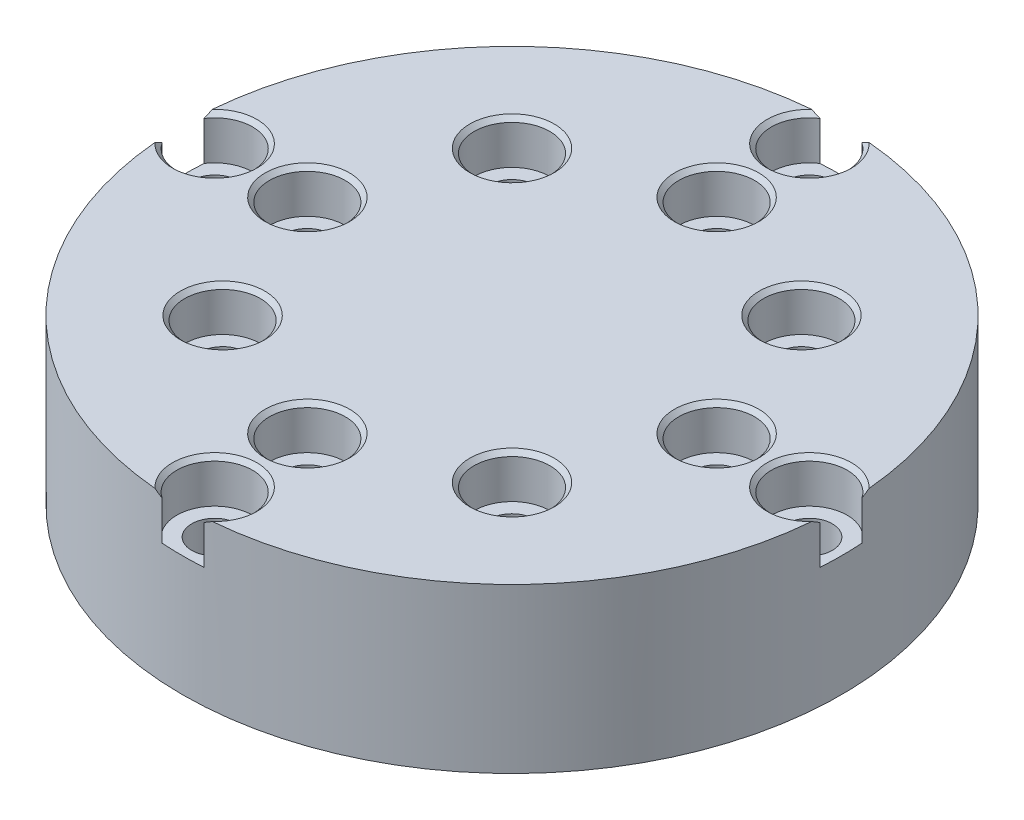
SolidWorks part; units mm, degrees
ref_plane "Front Plane" through (0, 0, 0) normal (0, 0, 1) x (1, 0, 0)
ref_plane "Top Plane" through (0, 0, 0) normal (0, 1, 0) x (1, 0, 0)
ref_plane "Right Plane" through (0, 0, 0) normal (1, 0, 0) x (0, 0, -1)
sketch "Sketch1" plane through (0, 0, 0) normal (0, 1, 0) x (1, 0, 0)
  circle A0 centre (0, 0) radius 48.3128
extrude "Boss-Extrude1" add sketch "Sketch1" along normal blind 24
sketch "Sketch2" plane through (0, 24, 0) normal (0, 1, 0) x (1, 0, 0)
  line L1 (24.7068, -14.1367) -> (-24.7068, -14.1367)
  line L2 (24.7068, -14.1367) -> (24.7068, 14.1367)
  line L3 (24.7068, 14.1367) -> (-24.7068, 14.1367)
  line L4 (-24.7068, -14.1367) -> (-24.7068, 14.1367)
  line L5 (24.7068, -14.1367) -> (-24.7068, 14.1367) construction
  line L6 (24.7068, 14.1367) -> (-24.7068, -14.1367) construction
  point P0 (0, 0)
hole_wizard "CBORE for 1/4 Socket Head Cap Screw1" positions "3DSketch1" profile "Sketch3" counterbore size "1/4" standard "ANSI Inch"
sketch3d "3DSketch1"
  line L0 (0, 24, 10) -> (0, 24, -10) construction
  point P2 (0, 24, 10)
  point P4 (-24.7068, 24, 14.1367)
  point P6 (-24.7068, 24, -14.1367)
  point P8 (24.7068, 24, -14.1367)
  point P10 (0, 24, -10)
  point P12 (24.7068, 24, 14.1367)
  point P31 (-12, 24, -0.1211)
  dimension "D1" = 20
  dimension "D2" = 12
sketch "Sketch3" plane through (0, 24, 10) normal (1, 0, 0) x (0, 0, 1)
  line L0 (0, 0) -> (0, 24)
  line L1 (0, 24) -> (3.3782, 24)
  line L3 (3.3782, 24) -> (3.3782, 6.35)
  line L4 (5.5562, 6.35) -> (3.3782, 6.35)
  line L5 (5.5562, 6.35) -> (5.5562, 0.635)
  line L6 (5.5562, 0.635) -> (6.1913, 0)
  line L7 (6.1913, 0) -> (0, 0)
  line L8 (-5.5562, 0.635) -> (-6.1913, 0) construction
  line L11 (0, -6.35) -> (0, 107.95) construction
  dimension "Thru Hole Dia." = 6.7564
  dimension "Thru Hole Depth" = 24
  dimension "C'Bore Dia." = 11.1125
  dimension "C'Bore Depth" = 6.35
  dimension "Near C'Sink Dia." = 12.3825
  dimension "Near C'Sink Angle" = 90
sketch "Sketch6" plane through (0, 24, 0) normal (0, 1, 0) x (1, 0, 0)
  line L0 (0, 43.5832) -> (0, -43.5832) construction
  line L1 (-43.5832, 0) -> (43.5832, 0) construction
  circle A0 centre (0, 0) radius 43.5832
  point P7 (30, 0)
  dimension "D1" = 30
hole_wizard "CBORE for 1/4 Socket Head Cap Screw2" positions "Sketch7" profile "Sketch8" counterbore size "1/4" standard "ANSI Inch" end condition up to next
sketch "Sketch7" plane through (0, 24, 0) normal (0, 1, 0) x (1, 0, 0)
  point P0 (0, 43.5832)
  point P3 (-43.5832, 0)
  point P6 (0, -43.5832)
  point P9 (43.5832, 0)
sketch "Sketch8" plane through (0, 24, -43.5832) normal (1, 0, 0) x (0, 0, 1)
  line L0 (0, 0) -> (0, 24)
  line L1 (0, 24) -> (3.3782, 24)
  line L3 (3.3782, 24) -> (3.3782, 6.35)
  line L4 (5.5562, 6.35) -> (3.3782, 6.35)
  line L5 (5.5562, 6.35) -> (5.5562, 0.635)
  line L6 (5.5562, 0.635) -> (6.1912, 0)
  line L7 (6.1912, 0) -> (0, 0)
  line L8 (-5.5562, 0.635) -> (-6.1912, 0) construction
  line L11 (0, -6.35) -> (0, 107.95) construction
  dimension "Thru Hole Dia." = 6.7564
  dimension "Thru Hole Depth" = 24
  dimension "C'Bore Dia." = 11.1125
  dimension "C'Bore Depth" = 6.35
  dimension "Near C'Sink Dia." = 12.3825
  dimension "Near C'Sink Angle" = 90
hole_wizard "CBORE for 1/4 Socket Head Cap Screw3" positions "Sketch9" profile "Sketch10" counterbore size "1/4" standard "ANSI Inch" end condition up to next
sketch "Sketch9" plane through (0, 24, 0) normal (0, 1, 0) x (1, 0, 0)
  point P0 (30, 0)
sketch "Sketch10" plane through (30, 24, 0) normal (1, 0, 0) x (0, 0, 1)
  line L0 (0, 0) -> (0, 24)
  line L1 (0, 24) -> (3.3782, 24)
  line L3 (3.3782, 24) -> (3.3782, 6.35)
  line L4 (5.5562, 6.35) -> (3.3782, 6.35)
  line L5 (5.5562, 6.35) -> (5.5562, 0.635)
  line L6 (5.5562, 0.635) -> (6.1912, 0)
  line L7 (6.1912, 0) -> (0, 0)
  line L8 (-5.5562, 0.635) -> (-6.1912, 0) construction
  line L11 (0, -6.35) -> (0, 107.95) construction
  dimension "Thru Hole Dia." = 6.7564
  dimension "Thru Hole Depth" = 24
  dimension "C'Bore Dia." = 11.1125
  dimension "C'Bore Depth" = 6.35
  dimension "Near C'Sink Dia." = 12.3825
  dimension "Near C'Sink Angle" = 90
pattern_circular "CirPattern1" count 8 over 360 about axis through (0, 0, 0) along (0, 1, 0) of "CBORE for 1/4 Socket Head Cap Screw3"
